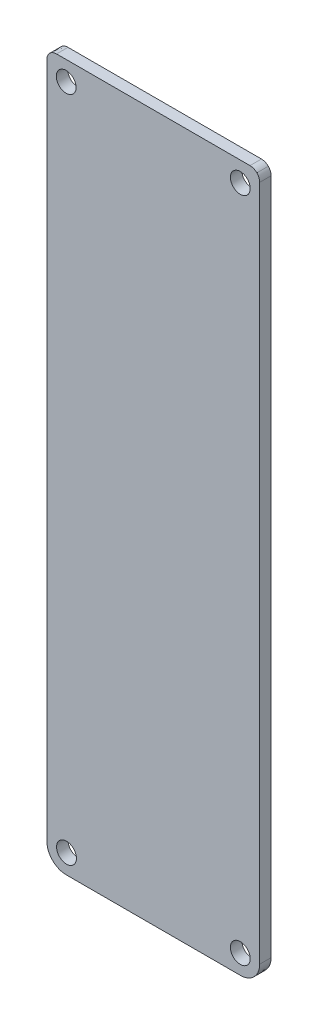
SolidWorks part; units mm, degrees
material "Plastique personnalisé"
ref_plane "Plan de face" through (0, 0, 0) normal (0, 0, 1) x (1, 0, 0)
ref_plane "Plan de dessus" through (0, 0, 0) normal (0, 1, 0) x (1, 0, 0)
ref_plane "Plan de droite" through (0, 0, 0) normal (1, 0, 0) x (0, 0, -1)
sketch "Model" plane through (0, 0, 0) normal (0, 0, 1) x (1, 0, 0)
  line L1773 (110.49, -34.8139) -> (110.49, -38.6239)
  line L1774 (83.82, -33.5439) -> (109.22, -33.5439)
  line L1775 (82.55, -38.6239) -> (82.55, -34.8139)
  line L1776 (82.55, -39.8939) -> (82.55, -123.7139)
  line L1777 (110.49, -39.8939) -> (110.49, -123.7139)
  line L1778 (82.55, -39.8939) -> (82.55, -38.6239)
  line L1779 (110.49, -39.8939) -> (110.49, -38.6239)
  line L1780 (85.09, -126.2539) -> (107.95, -126.2539)
  spline S12 degree 3 poles (110.49, -34.8139) (110.49, -34.4771) (110.3562, -34.1541) (110.118, -33.9159) knots 0 0 0 0 1 1 1 1
  spline S13 degree 3 poles (110.118, -33.9159) (109.8799, -33.6777) (109.5568, -33.5439) (109.22, -33.5439) knots 0 0 0 0 1 1 1 1
  spline S14 degree 3 poles (83.82, -33.5439) (83.4832, -33.5439) (83.1601, -33.6777) (82.922, -33.9159) knots 0 0 0 0 1 1 1 1
  spline S15 degree 3 poles (82.922, -33.9159) (82.6838, -34.1541) (82.55, -34.4771) (82.55, -34.8139) knots 0 0 0 0 1 1 1 1
  spline S16 degree 3 poles (82.55, -123.7139) (82.55, -124.3876) (82.8176, -125.0336) (83.2939, -125.51) knots 0 0 0 0 1 1 1 1
  spline S17 degree 3 poles (83.2939, -125.51) (83.7703, -125.9863) (84.4163, -126.2539) (85.09, -126.2539) knots 0 0 0 0 1 1 1 1
  spline S18 degree 3 poles (107.95, -126.2539) (108.6236, -126.2539) (109.2697, -125.9863) (109.7461, -125.51) knots 0 0 0 0 1 1 1 1
  spline S19 degree 3 poles (109.7461, -125.51) (110.2224, -125.0336) (110.49, -124.3876) (110.49, -123.7139) knots 0 0 0 0 1 1 1 1
extrude "Boss.-Extru.1" add sketch "Model" along normal blind 1.5
sketch "Esquisse2" plane through (0, 0, 1.5) normal (0, 0, 1) x (1, 0, 0)
  circle A0 centre (85.1248, -123.7139) radius 1.3048
  circle A1 centre (122.9136, -132.3177) radius 1.27
extrude "Enlèv. mat.-Extru.1" cut sketch "Esquisse2" against normal blind 10
sketch "Esquisse3" plane through (0, 0, 1.5) normal (0, 0, 1) x (1, 0, 0)
  circle A2 centre (107.9434, -36.1486) radius 1.3
  circle A3 centre (85.0841, -36.0913) radius 1.3
  circle A4 centre (107.9434, -123.7139) radius 1.3
  dimension "D1" = 2.6
extrude "Enlèv. mat.-Extru.2" cut sketch "Esquisse3" against normal blind 10
sketch "Esquisse4" plane through (0, 0, 0) normal (0, 0, -1) x (-1, 0, 0)
  line L0 (-107.9434, -36.1486) -> (-107.9434, -123.7139) construction
